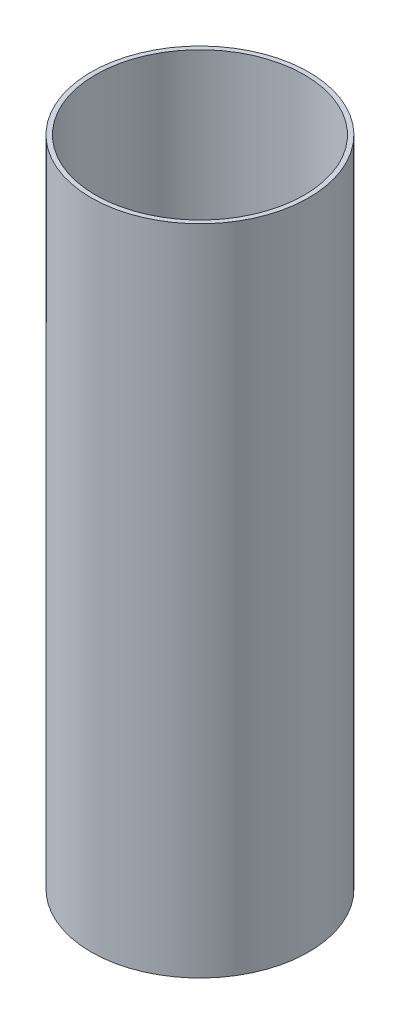
SolidWorks part; units mm, degrees
ref_plane "Front Plane" through (0, 0, 0) normal (0, 0, 1) x (1, 0, 0)
ref_plane "Top Plane" through (0, 0, 0) normal (0, 1, 0) x (1, 0, 0)
ref_plane "Right Plane" through (0, 0, 0) normal (1, 0, 0) x (0, 0, -1)
sketch "Sketch1" plane through (0, 0, 0) normal (0, 1, 0) x (1, 0, 0)
  circle A0 centre (0, 0) radius 73.025
  circle A1 centre (0, 0) radius 76.2
  dimension "D1" = 146.05
  dimension "D2" = 152.4
extrude "Boss-Extrude1" add sketch "Sketch1" along normal blind 457.2
